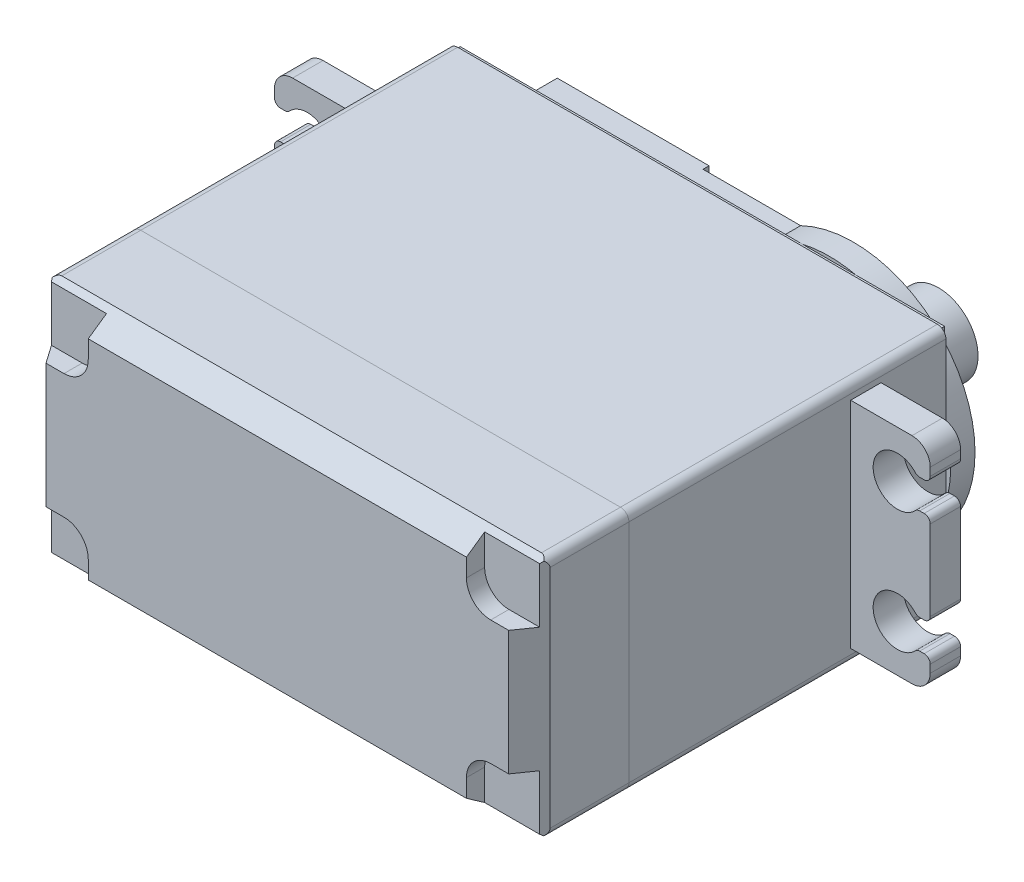
SolidWorks part; units mm, degrees
ref_plane "Front Plane" through (0, 0, 0) normal (0, 0, 1) x (1, 0, 0)
ref_plane "Top Plane" through (0, 0, 0) normal (0, 1, 0) x (1, 0, 0)
ref_plane "Right Plane" through (0, 0, 0) normal (1, 0, 0) x (0, 0, -1)
sketch "Sketch1" plane through (0, 0, 0) normal (0, 0, 1) x (1, 0, 0)
  line L1 (20.45, -10) -> (-20.45, -10)
  line L2 (20.45, -10) -> (20.45, 10)
  line L3 (20.45, 10) -> (-20.45, 10)
  line L4 (-20.45, -10) -> (-20.45, 10)
  line L5 (20.45, -10) -> (-20.45, 10) construction
  line L6 (20.45, 10) -> (-20.45, -10) construction
  point P0 (0, 0)
  dimension "D1" = 40.9
  dimension "D2" = 20
extrude "Boss-Extrude1" add sketch "Sketch1" along normal blind 19.3
sketch "Sketch3" plane through (0, 0, 0) normal (0, 0, -1) x (-1, 0, 0)
  line L4 (20.45, -10) -> (20.45, 10)
  line L5 (20.45, 10) -> (-20.45, 10)
  line L6 (-20.45, 10) -> (-20.45, -10)
  line L7 (-20.45, -10) -> (20.45, -10)
  line L8 (20.45, -10) -> (20.45, 10)
  line L9 (20.45, 10) -> (-20.45, 10)
  line L10 (-20.45, 10) -> (-20.45, -10)
  line L11 (-20.45, -10) -> (20.45, -10)
  dimension "D1" = 0
extrude "Boss-Extrude2" add sketch "Sketch3" along normal blind 6.8 separate body
sketch "Sketch4" plane through (0, 0, 19.3) normal (0, 0, 1) x (1, 0, 0)
  line L4 (-20.45, 10) -> (-20.45, -10)
  line L5 (-20.45, -10) -> (20.45, -10)
  line L6 (20.45, -10) -> (20.45, 10)
  line L7 (20.45, 10) -> (-20.45, 10)
  line L8 (-20.45, 10) -> (-20.45, -10)
  line L9 (-20.45, -10) -> (20.45, -10)
  line L10 (20.45, -10) -> (20.45, 10)
  line L11 (20.45, 10) -> (-20.45, 10)
  dimension "D1" = 0
extrude "Boss-Extrude3" add sketch "Sketch4" along normal blind 8.5 separate body
chamfer "Chamfer1" distance 2 angle 35 4 edges at (20.45, 0, 27.8) (0, -10, 27.8) (-20.45, 0, 27.8) (0, 10, 27.8)
sketch "Sketch5" plane through (0, 0, 27.8) normal (0, 0, 1) x (1, 0, 0)
  line L0 (-20.45, 10) -> (-19.0496, 8.5996) construction
  line L1 (-20.45, 10) -> (-15.57, 10)
  line L2 (-20.45, 10) -> (-20.45, 5.12)
  line L3 (-20.45, 5.12) -> (-17.57, 5.12)
  line L4 (-15.57, 10) -> (-15.57, 7.12)
  line L5 (-20.45, 10) -> (20.45, 10) construction
  line L6 (0, 10) -> (0, -11.6443) construction
  line L7 (0, 0) -> (20.45, 0) construction
  line L8 (20.45, 10) -> (20.45, -10) construction
  line L9 (20.45, 5.12) -> (17.57, 5.12)
  line L10 (15.57, 10) -> (15.57, 7.12)
  line L11 (20.45, 10) -> (15.57, 10)
  line L12 (20.45, 10) -> (20.45, 5.12)
  line L13 (-20.45, -5.12) -> (-17.57, -5.12)
  line L14 (-15.57, -10) -> (-15.57, -7.12)
  line L15 (-20.45, -10) -> (-15.57, -10)
  line L16 (-20.45, -10) -> (-20.45, -5.12)
  line L17 (20.45, -10) -> (20.45, -5.12)
  line L18 (20.45, -10) -> (15.57, -10)
  line L19 (15.57, -10) -> (15.57, -7.12)
  line L20 (20.45, -5.12) -> (17.57, -5.12)
  arc A0 (-17.57, 5.12) -> (-15.57, 7.12) centre (-17.57, 7.12) ccw
  arc A1 (17.57, 5.12) -> (15.57, 7.12) centre (17.57, 7.12) cw
  arc A2 (-17.57, -5.12) -> (-15.57, -7.12) centre (-17.57, -7.12) cw
  arc A3 (17.57, -5.12) -> (15.57, -7.12) centre (17.57, -7.12) ccw
  point P10 (-15.57, 5.12)
  dimension "D3" = 2
  dimension "D1" = 4.88
  dimension "D2" = 4.88
extrude "Cut-Extrude1" cut sketch "Sketch5" against normal blind 1.5
sketch "Sketch6" plane through (0, 0, -6.8) normal (0, 0, -1) x (-1, 0, 0)
  line L1 (19.95, -9.75) -> (-19.95, -9.75)
  line L2 (19.95, -9.75) -> (19.95, 9.75)
  line L3 (19.95, 9.75) -> (-19.95, 9.75)
  line L4 (-19.95, -9.75) -> (-19.95, 9.75)
  line L5 (19.95, -9.75) -> (-19.95, 9.75) construction
  line L6 (19.95, 9.75) -> (-19.95, -9.75) construction
  point P0 (0, 0)
  dimension "D1" = 0.25
  dimension "D2" = 0.5
extrude "Boss-Extrude4" add sketch "Sketch6" along normal blind 0.4
sketch "Sketch7" plane through (0, 0, -7.2) normal (0, 0, -1) x (-1, 0, 0)
  line L0 (-20.45, 0) -> (20.45, 0) construction
  line L1 (-20.45, 10) -> (-20.45, -10) construction
  line L2 (20.45, -10) -> (20.45, 10) construction
  line L3 (20.45, 10) -> (-20.45, 10) construction
  line L4 (-6.09, 10) -> (-6.09, -9.75) construction
  line L5 (-19.95, -9.75) -> (19.95, -9.75) construction
  line L6 (-6.09, 8.9995) -> (14.45, 8.9995)
  line L7 (14.45, 8.9995) -> (14.45, 3)
  line L8 (-6.09, -8.9995) -> (14.45, -8.9995)
  line L9 (14.45, -8.9995) -> (14.45, -3)
  arc A0 (-6.09, 8.9995) -> (-6.09, -8.9995) centre (-10.45, 0) ccw
  arc A1 (14.45, -3) -> (14.45, 3) centre (14.45, 0) ccw
  point P18 (17.45, 0)
  dimension "D1" = 14.36
  dimension "D2" = 6
  dimension "D3" = 3
extrude "Boss-Extrude5" add sketch "Sketch7" along normal blind 2
sketch "Sketch8" plane through (0, 0, -9.2) normal (0, 0, -1) x (-1, 0, 0)
  circle A0 centre (-10.45, 0) radius 6.5
  dimension "D1" = 13
extrude "Boss-Extrude6" add sketch "Sketch8" along normal blind 1.5
sketch "Sketch9" plane through (0, 0, -10.7) normal (0, 0, -1) x (-1, 0, 0)
  circle A0 centre (-10.45, 0) radius 5.5
  dimension "D1" = 11
extrude "Boss-Extrude8" add sketch "Sketch9" along normal blind 0.5
sketch "Sketch11" plane through (0, 0, -11.2) normal (0, 0, -1) x (-1, 0, 0)
  circle A0 centre (-10.45, 0) radius 3.25
  dimension "D1" = 6.5
extrude "Boss-Extrude9" add sketch "Sketch11" along normal blind 5
sketch "Sketch12" plane through (0, 0, -9.2) normal (0, 0, -1) x (-1, 0, 0)
  line L0 (-6.09, -8.9995) -> (14.45, -8.9995) construction
  line L1 (14.45, 8.9995) -> (1.95, 8.9995)
  line L2 (14.45, 8.9995) -> (14.45, -8.9995)
  line L3 (14.45, -8.9995) -> (1.95, -8.9995)
  line L4 (1.95, 8.9995) -> (1.95, 1.75)
  line L5 (2.95, 7.9995) -> (2.95, -7.9995)
  line L6 (13.45, -7.9995) -> (2.95, -7.9995)
  line L7 (13.45, 7.9995) -> (13.45, -7.9995)
  line L8 (13.45, 7.9995) -> (2.95, 7.9995)
  line L10 (1.95, -1.75) -> (1.95, -8.9995)
  line L12 (1.95, 8.9995) -> (1.95, -8.9995) construction
  arc A0 (1.95, 1.75) -> (1.95, -1.75) centre (1.95, 0) ccw
  dimension "D3" = 3.5
  dimension "D1" = 12.5
  dimension "D2" = 1
extrude "Boss-Extrude10" add sketch "Sketch12" along normal blind 0.5
fillet "Fillet1" radius 0.7 4 edges at (-20.45, -10, 9.65) (-20.45, 10, 9.65) (20.45, 10, 9.65) (20.45, -10, 9.65)
fillet "Fillet2" radius 0.7 4 edges at (-20.45, 10, -3.4) (-20.45, -10, -3.4) (20.45, -10, -3.4) (20.45, 10, -3.4)
fillet "Fillet3" radius 0.7 4 edges at (20.45, 10, 22.55) (-20.45, 10, 22.55) (-20.45, -10, 22.55) (20.45, -10, 22.55)
sketch "Sketch13" plane through (0, 0, -7.2) normal (0, 0, -1) x (-1, 0, 0)
  line L0 (20.45, 8.85) -> (25.5, 8.85)
  line L1 (20.45, -9.3) -> (20.45, 9.3) construction
  line L2 (27, 7.35) -> (27, 6.7)
  line L3 (0, 0) -> (27, 0) construction
  line L4 (19.75, 10) -> (-19.75, 10) construction
  line L5 (25.9, 8.85) -> (25.9, 0) construction
  line L6 (26.133, 6.2) -> (26.5, 6.2)
  line L7 (26.133, 3.8) -> (26.5, 3.8)
  line L8 (27, 3.3) -> (27, -3.3)
  line L9 (20.45, -8.85) -> (25.5, -8.85)
  line L10 (26.133, -3.8) -> (26.5, -3.8)
  line L11 (26.133, -6.2) -> (26.5, -6.2)
  line L12 (27, -7.35) -> (27, -6.7)
  line L13 (20.45, 8.85) -> (20.45, -8.85)
  arc A0 (25.7664, 6.36) -> (25.7664, 3.64) centre (24.3, 5) ccw
  arc A1 (25.7664, 3.64) -> (26.133, 3.8) centre (26.133, 3.3) cw
  arc A2 (25.7664, 6.36) -> (26.133, 6.2) centre (26.133, 6.7) ccw
  arc A3 (26.5, 3.8) -> (27, 3.3) centre (26.5, 3.3) cw
  arc A4 (26.5, 6.2) -> (27, 6.7) centre (26.5, 6.7) ccw
  arc A5 (25.5, 8.85) -> (27, 7.35) centre (25.5, 7.35) cw
  arc A6 (25.5, -8.85) -> (27, -7.35) centre (25.5, -7.35) ccw
  arc A7 (26.5, -6.2) -> (27, -6.7) centre (26.5, -6.7) cw
  arc A8 (26.5, -3.8) -> (27, -3.3) centre (26.5, -3.3) ccw
  arc A9 (25.7664, -6.36) -> (26.133, -6.2) centre (26.133, -6.7) cw
  arc A10 (25.7664, -3.64) -> (26.133, -3.8) centre (26.133, -3.3) ccw
  arc A11 (25.7664, -6.36) -> (25.7664, -3.64) centre (24.3, -5) cw
  point P18 (25.9, 3.8)
  point P21 (25.9, 6.2)
  point P24 (27, 3.8)
  point P29 (27, 8.85)
  point P47 (27, -8.85)
  point P48 (27, -3.8)
  point P49 (25.9, -6.2)
  point P50 (25.9, -3.8)
  dimension "D3" = 4
  dimension "D7" = 0.5
  dimension "D8" = 1.5
  dimension "D1" = 6.55
  dimension "D2" = 1.15
  dimension "D4" = 5
  dimension "D5" = 24.3
  dimension "D6" = 1.1
extrude "Boss-Extrude11" add sketch "Sketch13" against normal blind 2.5 from offset 5.74 offset against normal yes
mirror "Mirror1" about plane through (0, 0, 0) normal (1, 0, 0) of "Boss-Extrude11"
